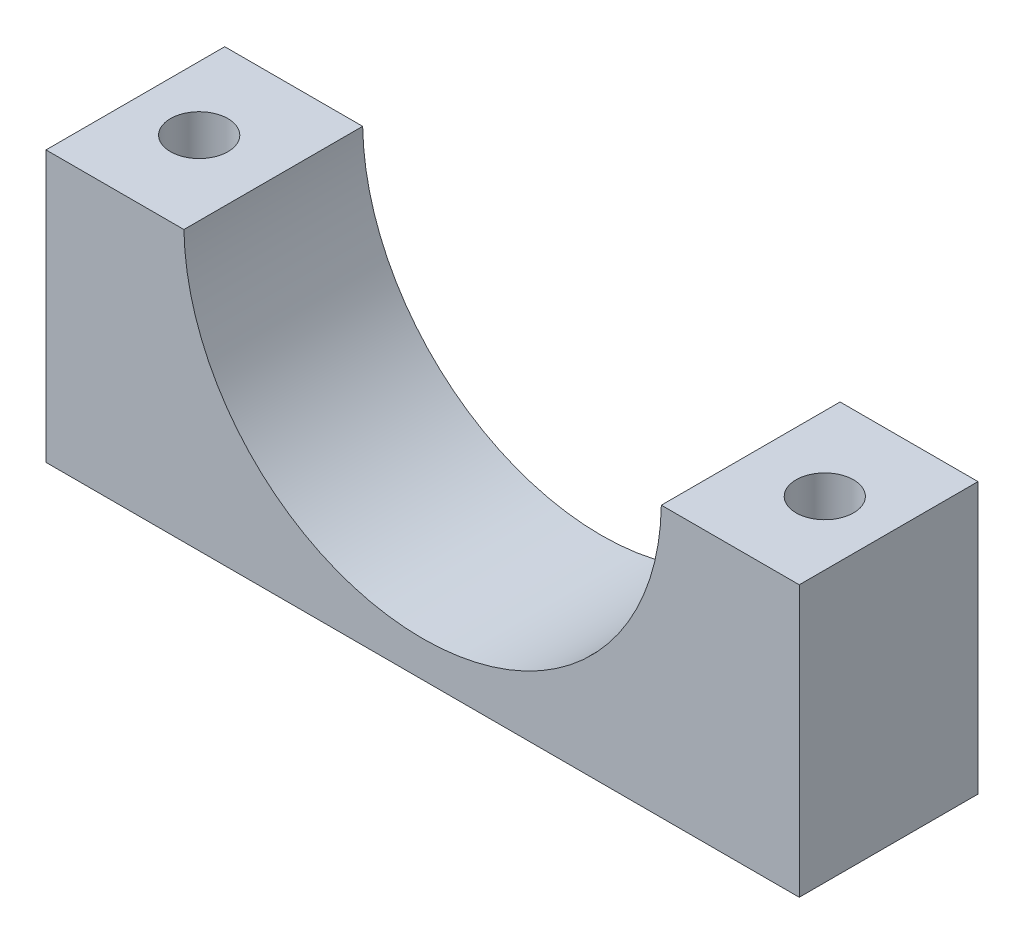
SolidWorks part; units mm, degrees
ref_plane "Front Plane" through (0, 0, 0) normal (0, 0, 1) x (1, 0, 0)
ref_plane "Top Plane" through (0, 0, 0) normal (0, 1, 0) x (1, 0, 0)
ref_plane "Right Plane" through (0, 0, 0) normal (1, 0, 0) x (0, 0, -1)
sketch "Split saddle with 37.4 mm bore profile" plane through (0, 0, 0) normal (0, 0, 1) x (1, 0, 0)
  line L0 (-29.5, 7) -> (29.5, 7)
  line L1 (29.5, 7) -> (29.5, 28.2)
  line L2 (29.5, 28.2) -> (18.6976, 28.2)
  line L3 (-18.6976, 28.2) -> (-29.5, 28.2)
  line L4 (-29.5, 28.2) -> (-29.5, 7)
  arc A0 (18.6976, 28.2) -> (-18.6976, 28.2) centre (0, 28.5) cw
extrude "Split saddle with 37.4 mm bore" add sketch "Split saddle with 37.4 mm bore profile" along normal blind 14
sketch "Sketch2" plane through (0, 0, 0) normal (0, 1, 0) x (1, 0, 0)
  circle A0 centre (-24.5, -7) radius 2.25
  circle A1 centre (24.5, -7) radius 2.25
extrude "M4 through holes" cut sketch "Sketch2" against normal through all and the other way through all
